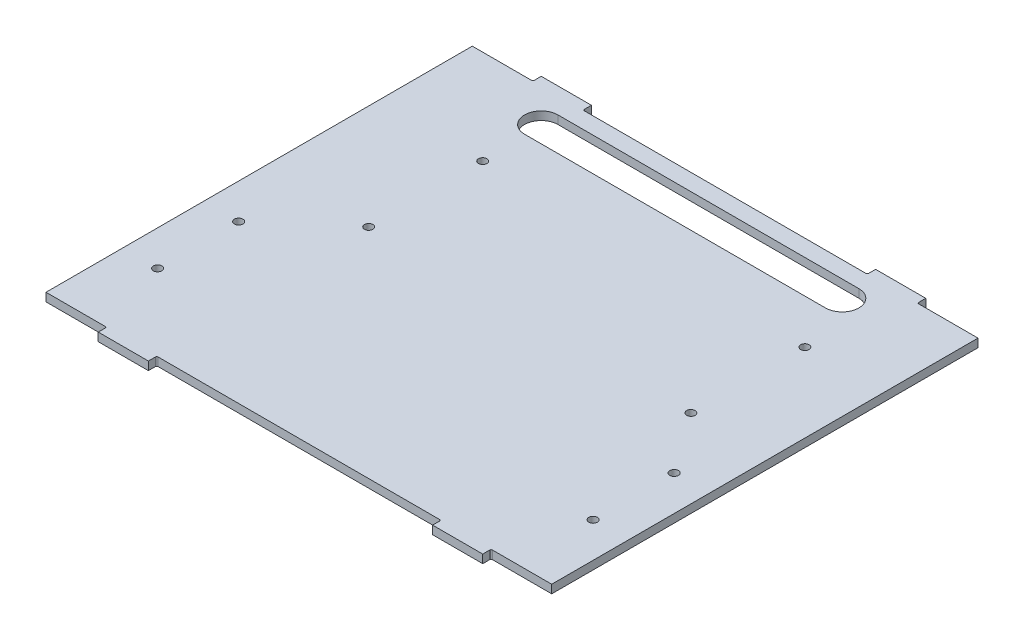
SolidWorks part; units mm, degrees
ref_plane "Front Plane" through (0, 0, 0) normal (0, 0, 1) x (1, 0, 0)
ref_plane "Top Plane" through (0, 0, 0) normal (0, 1, 0) x (1, 0, 0)
ref_plane "Right Plane" through (0, 0, 0) normal (1, 0, 0) x (0, 0, -1)
sketch "Sketch1" plane through (0, 0, 0) normal (0, 1, 0) x (1, 0, 0)
  line L1 (-96.0438, 80.9625) -> (96.0438, 80.9625)
  line L2 (-96.0438, 80.9625) -> (-96.0437, -80.9625)
  line L3 (-96.0437, -80.9625) -> (96.0438, -80.9625)
  line L4 (96.0438, 80.9625) -> (96.0438, -80.9625)
  point P4 (-96.0437, 0)
  point P6 (0, 80.9625)
  dimension "D1" = 161.925
  dimension "D2" = 192.0875
extrude "Boss-Extrude1" add sketch "Sketch1" along normal blind 3.175
sketch "Sketch2" plane through (0, 3.175, 0) normal (0, 1, 0) x (1, 0, 0)
  line L0 (96.0438, 80.9625) -> (-96.0438, 80.9625) construction
  line L1 (-73.025, 84.1375) -> (-53.975, 84.1375)
  line L2 (-73.025, 84.1375) -> (-73.025, 80.9625)
  line L3 (-73.025, 80.9625) -> (-53.975, 80.9625)
  line L4 (-53.975, 84.1375) -> (-53.975, 80.9625)
  line L5 (0, 0) -> (0, 50000) construction
  line L6 (53.975, 84.1375) -> (73.025, 84.1375)
  line L7 (53.975, 84.1375) -> (53.975, 80.9625)
  line L8 (53.975, 80.9625) -> (73.025, 80.9625)
  line L9 (73.025, 84.1375) -> (73.025, 80.9625)
  line L10 (-96.0437, -80.9625) -> (96.0438, -80.9625) construction
  line L11 (-73.025, -80.9625) -> (-53.975, -80.9625)
  line L12 (-73.025, -80.9625) -> (-73.025, -84.1375)
  line L13 (-73.025, -84.1375) -> (-53.975, -84.1375)
  line L14 (-53.975, -80.9625) -> (-53.975, -84.1375)
  line L16 (53.975, -80.9625) -> (73.025, -80.9625)
  line L17 (53.975, -80.9625) -> (53.975, -84.1375)
  line L18 (53.975, -84.1375) -> (73.025, -84.1375)
  line L19 (73.025, -80.9625) -> (73.025, -84.1375)
  dimension "D1" = 19.05
  dimension "D2" = 107.95
  dimension "D3" = 3.175
  dimension "D4" = 3.175
extrude "Boss-Extrude2" add sketch "Sketch2" against normal up to surface (3.175 mm away) up to face at (0, 0, 0)
sketch "Sketch3" plane through (0, 3.175, 0) normal (0, 1, 0) x (1, 0, 0)
  line L0 (-57.15, 68.2625) -> (57.15, 68.2625) construction
  line L1 (-57.15, 74.6125) -> (57.15, 74.6125)
  line L2 (-57.15, 61.9125) -> (57.15, 61.9125)
  line L4 (53.975, 80.9625) -> (-53.975, 80.9625) construction
  arc A0 (-57.15, 74.6125) -> (-57.15, 61.9125) centre (-57.15, 68.2625) ccw
  arc A1 (57.15, 61.9125) -> (57.15, 74.6125) centre (57.15, 68.2625) ccw
  point P2 (0, 68.2625)
  dimension "D2" = 6.35
  dimension "D1" = 114.3
  dimension "D3" = 12.7
extrude "Cut-Extrude1" cut sketch "Sketch3" against normal through all
fillet "Fillet1" radius 0.508 8 edges at (73.025, 1.5875, 80.9625) (53.975, 1.5875, 80.9625) (53.975, 1.5875, -80.9625) (73.025, 1.5875, -80.9625)
sketch "Sketch4" plane through (0, 0, 0) normal (0, -1, 0) x (1, 0, 0)
  circle A0 centre (-82.7024, 51.9049) radius 1.6256
  circle A1 centre (-82.7024, 21.1201) radius 1.6256
  circle A2 centre (82.7024, 21.1201) radius 1.6256
  circle A3 centre (82.7024, 51.9049) radius 1.6256
  circle A4 centre (-82.7024, 51.9049) radius 1.6256 construction
extrude "Cut-Extrude2" cut sketch "Sketch4" against normal up to next
sketch "Sketch5" plane through (0, 3.175, 0) normal (0, 1, 0) x (1, 0, 0)
  circle A0 centre (66.1333, 1.8125) radius 1.6
  circle A1 centre (66.1333, 45.1125) radius 1.6
  circle A2 centre (-56.25, 45.1125) radius 1.6
  circle A3 centre (-56.25, 1.8125) radius 1.6
  arc A4 (67.7333, 1.8125) -> (64.5333, 1.8125) centre (66.1333, 1.8125) ccw construction
extrude "Cut-Extrude3" cut sketch "Sketch5" against normal up to next
